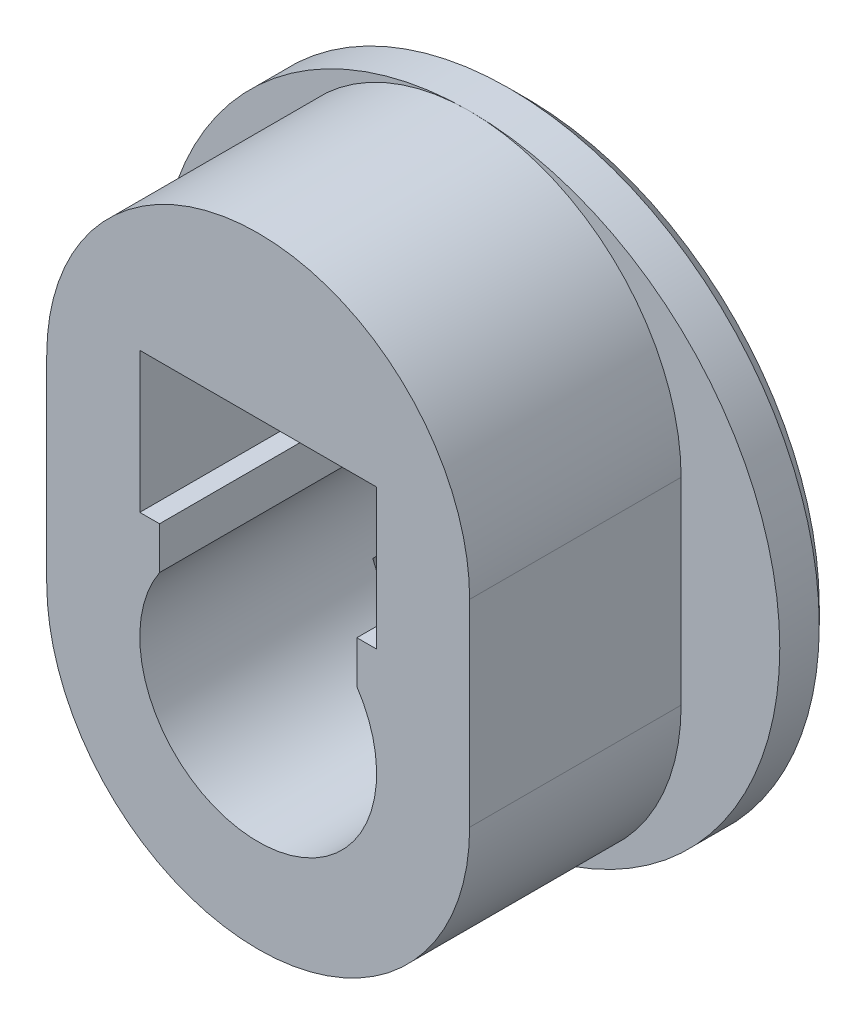
SolidWorks part; units mm, degrees
material "ABS"
ref_plane "Front" through (0, 0, 0) normal (0, 0, 1) x (1, 0, 0)
ref_plane "Top" through (0, 0, 0) normal (0, 1, 0) x (1, 0, 0)
ref_plane "Right" through (0, 0, 0) normal (1, 0, 0) x (0, 0, -1)
sketch "Эскиз7" plane through (0, 0, 0) normal (0, 0, 1) x (1, 0, 0)
  line L0 (0, 0) -> (0, 7) construction
  line L1 (-7.5, 0) -> (-7.5, 7)
  line L2 (7.5, 0) -> (7.5, 7)
  circle A0 centre (0, 0) radius 4.2 construction
  arc A1 (-7.5, 0) -> (7.5, 0) centre (0, 0) ccw
  arc A2 (7.5, 7) -> (-7.5, 7) centre (0, 7) ccw
  point P5 (0, 3.5)
  dimension "D1" = 8.4
  dimension "D2" = 15
  dimension "D3" = 7
extrude "Бобышка-Вытянуть1" add sketch "Эскиз7" along normal blind 9.5
sketch "Эскиз8" plane through (0, 0, 0) normal (0, 0, -1) x (-1, 0, 0)
  line L0 (0, 3.5) -> (0, 0) construction
  circle A0 centre (0, 3.5) radius 11
  arc A2 (-7.5, 0) -> (7.5, 0) centre (0, 0) ccw construction
  arc A3 (7.5, 7) -> (-7.5, 7) centre (0, 7) ccw construction
  dimension "D1" = 3.5
extrude "Бобышка-Вытянуть2" add sketch "Эскиз8" against normal blind 2
sketch "Эскиз3" plane through (0, 0, 0) normal (0, 0, -1) x (-1, 0, 0)
  line L0 (-4.2, -4.2) -> (4.2, -4.2) construction
  line L1 (-4.2, 8.8) -> (4.2, 8.8)
  line L2 (-4.2, 8.8) -> (-4.2, 3.8216)
  line L4 (4.2, 8.8) -> (4.2, 3.8216)
  line L5 (-3.5, 3.8216) -> (-4.2, 3.8216)
  line L6 (3.5, 3.8216) -> (4.2, 3.8216)
  line L7 (-3.5, 2.3216) -> (3.5, 2.3216) construction
  line L8 (-4.2, 3.8216) -> (-4.2, -4.2) construction
  line L9 (3.5, 2.3216) -> (3.5, 3.8216)
  line L10 (4.2, -4.2) -> (4.2, 3.8216) construction
  line L11 (-3.5, 2.3216) -> (-3.5, 3.8216)
  arc A1 (3.5, 2.3216) -> (-3.5, 2.3216) centre (0, 0) cw
  dimension "D3" = 7
  dimension "D1" = 13
  dimension "D2" = 8.4
  dimension "D4" = 1.5
extrude "Вырез под двигатель" cut sketch "Эскиз3" against normal through all
sketch "Эскиз6" plane through (0, 0, 0) normal (0, 0, -1) x (-1, 0, 0)
  line L0 (-3.677, 3.677) -> (3.677, -3.677) construction
  line L1 (0, 0) -> (0, 2.6929) construction
  line L2 (3.677, 3.677) -> (-3.677, -3.677) construction
  arc A0 (-1.4623, 3.9372) -> (-3.9372, 1.4623) centre (-2.4049, 2.4049) ccw
  circle A1 centre (0, 0) radius 4.2 construction
  arc A2 (3.9372, -1.4623) -> (1.4623, -3.9372) centre (2.4049, -2.4049) cw
  arc A3 (3.9372, -1.4623) -> (1.4623, -3.9372) centre (0, 0) cw
  arc A4 (-1.4623, 3.9372) -> (-3.9372, 1.4623) centre (0, 0) ccw
  arc A5 (-1.4623, -3.9372) -> (-3.9372, -1.4623) centre (0, 0) cw
  arc A6 (1.4623, 3.9372) -> (3.9372, 1.4623) centre (0, 0) cw
  arc A7 (-1.4623, -3.9372) -> (-3.9372, -1.4623) centre (-2.4049, -2.4049) cw
  arc A8 (3.9372, 1.4623) -> (1.4623, 3.9372) centre (2.4049, 2.4049) ccw
  arc A9 (-3.5, 2.3216) -> (3.5, 2.3216) centre (0, 0) ccw construction
  point P2 (0, 0)
  point P9 (0, 0)
  point P12 (-1.4623, 3.9372)
  point P16 (3.677, -3.677)
  point P17 (-4.2861, 1.632)
  point P19 (0, 0)
  point P31 (0, 0)
  point P32 (0, 0)
  point P33 (0, 0)
  point P34 (0, 0)
  dimension "D1" = 3.5
  dimension "D2" = 10.4
  dimension "D3" = 45
extrude "Упор двигателя" cut sketch "Эскиз6" against normal blind 1.5
chamfer "Фаска1" distance 0.6 angle 45 13 edges at (-11, 3.5, 0) (-4.2, 6.3108, 0) (0, 8.8, 0) (4.2, 6.3108, 0) (3.8568, 3.8216, 0) (4.1756, 2.7228, 0) (4.2, 0, 0) (3.677, -3.677, 0) (0, -4.2, 0) (-3.677, -3.677, 0) (-4.2, 0, 0) (-4.1756, 2.7228, 0) (-3.8568, 3.8216, 0)
